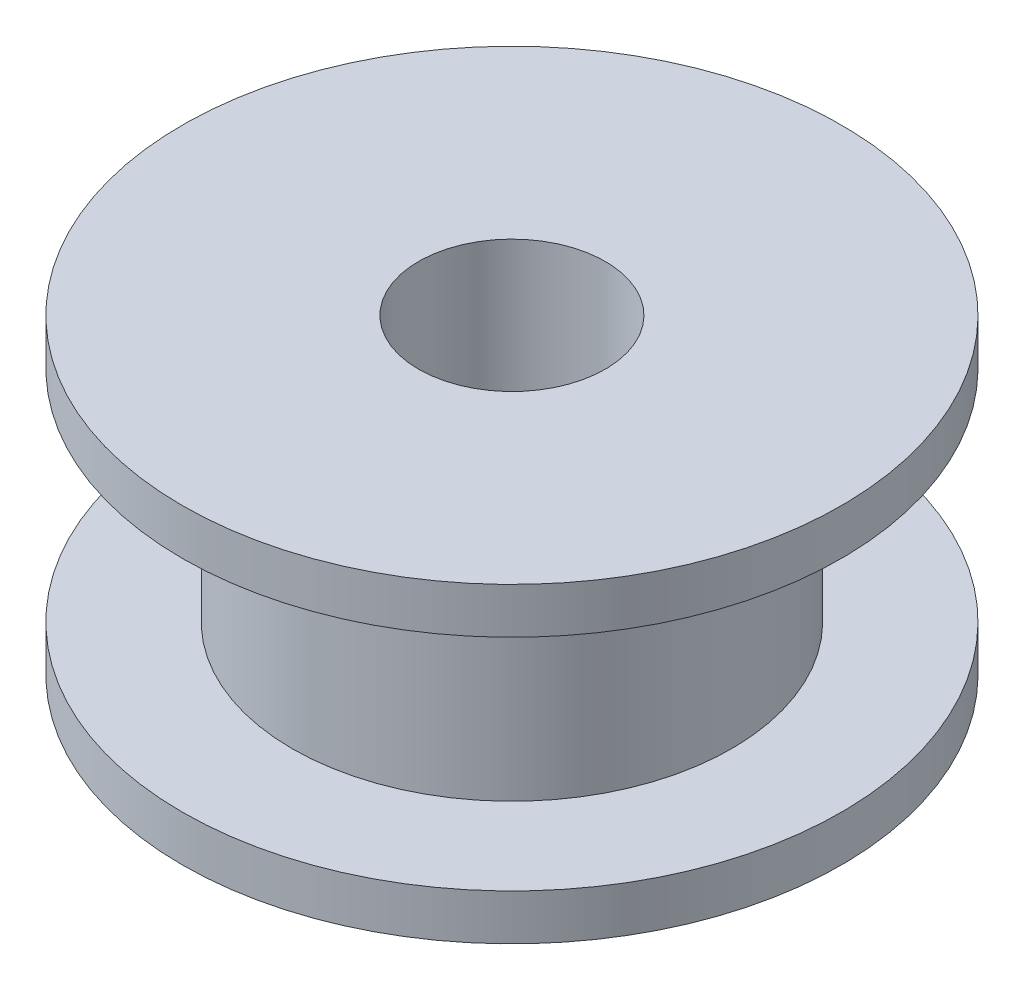
SolidWorks part; units mm, degrees
ref_plane "前视基准面" through (0, 0, 0) normal (0, 0, 1) x (1, 0, 0)
ref_plane "上视基准面" through (0, 0, 0) normal (0, 1, 0) x (1, 0, 0)
ref_plane "右视基准面" through (0, 0, 0) normal (1, 0, 0) x (0, 0, -1)
other "Configuration Table"
sketch "草图1" plane through (0, 0, 0) normal (0, 1, 0) x (1, 0, 0)
  circle A0 centre (0, 0) radius 6
  dimension "D1" = 12
extrude "凸台-拉伸1" add sketch "草图1" along normal mid plane 6
sketch "草图3" plane through (0, 3, 0) normal (0, 1, 0) x (1, 0, 0)
  circle A0 centre (0, 0) radius 9
  dimension "D1" = 18
extrude "凸台-拉伸2" add sketch "草图3" along normal blind 1.25
mirror "镜向1" about plane through (0, 0, 0) normal (0, 1, 0) of "凸台-拉伸2"
sketch "草图4" plane through (0, 4.25, 0) normal (0, 1, 0) x (1, 0, 0)
  circle A0 centre (0, 0) radius 2.55
  dimension "D1" = 5.1
extrude "切除-拉伸1" cut sketch "草图4" against normal through all
